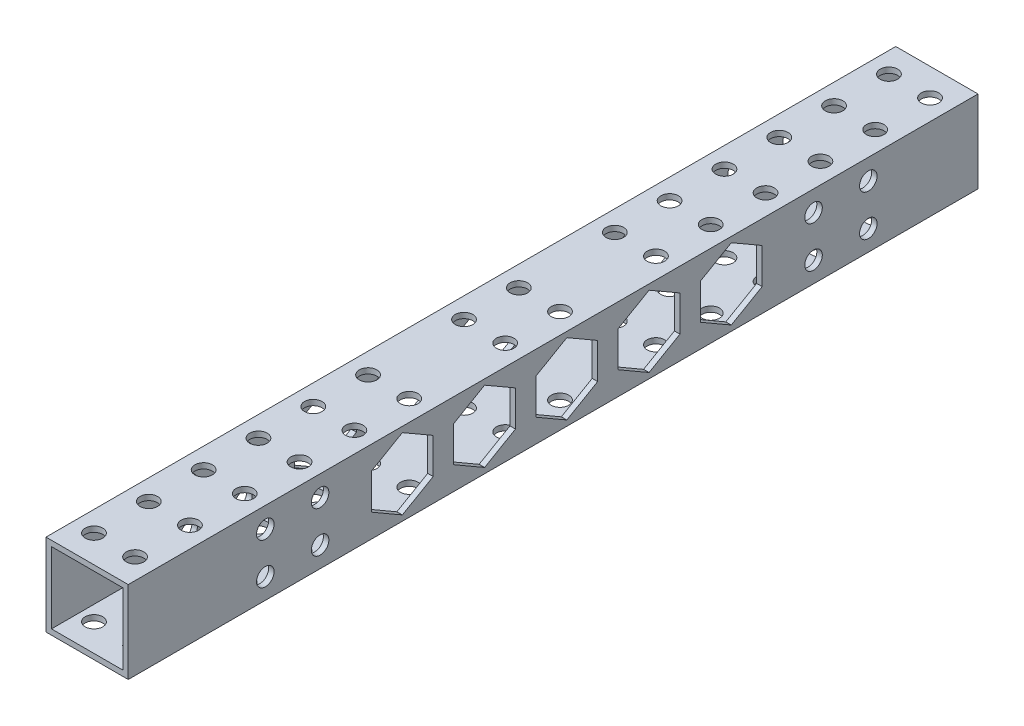
SolidWorks part; units mm, degrees
ref_plane "前视基准面" through (0, 0, 0) normal (0, 0, 1) x (1, 0, 0)
ref_plane "上视基准面" through (0, 0, 0) normal (0, 1, 0) x (1, 0, 0)
ref_plane "右视基准面" through (0, 0, 0) normal (1, 0, 0) x (0, 0, -1)
other "Configuration Table"
sketch "草图1" plane through (0, 0, 0) normal (0, 0, 1) x (1, 0, 0)
  line L1 (0, 0) -> (15, 0)
  line L2 (0, 0) -> (0, -15)
  line L3 (0, -15) -> (15, -15)
  line L4 (15, 0) -> (15, -15)
  dimension "D1" = 15
  dimension "D2" = 15
extrude "拉伸-薄壁1" add sketch "草图1" along normal blind 155 thin
sketch "草图2" plane through (15, 0, 0) normal (1, 0, 0) x (0, 0, -1)
  line L0 (-77.5, 0) -> (-77.5, -15) construction
  line L1 (-155, 0) -> (0, 0) construction
  line L2 (-155, -15) -> (0, -15) construction
  line L3 (-125, 0) -> (-125, -15) construction
  line L4 (-155, -15) -> (-155, 0) construction
  line L5 (-155, -7.5) -> (-125, -7.5) construction
  line L6 (-25, 0) -> (-25, -15) construction
  line L7 (0, -7.5) -> (-25, -7.5) construction
  line L8 (0, -15) -> (0, 0) construction
  line L9 (-105, -7.5) -> (-125, -7.5) construction
  line L10 (-105, -1) -> (-110.6292, -4.25)
  line L11 (-110.6292, -4.25) -> (-110.6292, -10.75)
  line L12 (-110.6292, -10.75) -> (-105, -14)
  line L13 (-105, -14) -> (-99.3708, -10.75)
  line L14 (-99.3708, -10.75) -> (-99.3708, -4.25)
  line L15 (-99.3708, -4.25) -> (-105, -1)
  line L16 (-84.3708, -10.75) -> (-84.3708, -4.25)
  line L17 (-84.3708, -4.25) -> (-90, -1)
  line L18 (-90, -1) -> (-95.6292, -4.25)
  line L19 (-95.6292, -4.25) -> (-95.6292, -10.75)
  line L20 (-95.6292, -10.75) -> (-90, -14)
  line L21 (-90, -14) -> (-84.3708, -10.75)
  line L22 (-69.3708, -10.75) -> (-69.3708, -4.25)
  line L23 (-69.3708, -4.25) -> (-75, -1)
  line L24 (-75, -1) -> (-80.6292, -4.25)
  line L25 (-80.6292, -4.25) -> (-80.6292, -10.75)
  line L26 (-80.6292, -10.75) -> (-75, -14)
  line L27 (-75, -14) -> (-69.3708, -10.75)
  line L28 (-54.3708, -10.75) -> (-54.3708, -4.25)
  line L29 (-54.3708, -4.25) -> (-60, -1)
  line L30 (-60, -1) -> (-65.6292, -4.25)
  line L31 (-65.6292, -4.25) -> (-65.6292, -10.75)
  line L32 (-65.6292, -10.75) -> (-60, -14)
  line L33 (-60, -14) -> (-54.3708, -10.75)
  line L34 (-39.3708, -10.75) -> (-39.3708, -4.25)
  line L35 (-39.3708, -4.25) -> (-45, -1)
  line L36 (-45, -1) -> (-50.6292, -4.25)
  line L37 (-50.6292, -4.25) -> (-50.6292, -10.75)
  line L38 (-50.6292, -10.75) -> (-45, -14)
  line L39 (-45, -14) -> (-39.3708, -10.75)
  circle A0 centre (-130, -3.75) radius 1.6
  circle A1 centre (-130, -11.25) radius 1.6
  circle A2 centre (-120, -11.25) radius 1.6
  circle A3 centre (-120, -3.75) radius 1.6
  circle A8 centre (-20, -3.75) radius 1.6
  circle A9 centre (-20, -11.25) radius 1.6
  circle A10 centre (-30, -11.25) radius 1.6
  circle A11 centre (-30, -3.75) radius 1.6
  circle A12 centre (-105, -7.5) radius 5.6292 construction
  dimension "D2" = 3.2
  dimension "D6" = 3.2
  dimension "D1" = 30
  dimension "D3" = 5
  dimension "D4" = 3.75
  dimension "D5" = 25
  dimension "D7" = 3.75
  dimension "D8" = 5
  dimension "D9" = 6.5
  dimension "D10" = 20
  dimension "D12" = 15
  dimension "D11" = 5
extrude "切除-拉伸1" cut sketch "草图2" against normal through all
sketch "草图3" plane through (0, 0, 0) normal (0, 1, 0) x (1, 0, 0)
  line L0 (7.5, 0) -> (7.5, -155) construction
  line L1 (15, 0) -> (0, 0) construction
  line L2 (15, -155) -> (0, -155) construction
  line L3 (15, -77.5) -> (0, -77.5) construction
  line L4 (15, -155) -> (15, 0) construction
  line L5 (0, -155) -> (0, 0) construction
  line L6 (0, -10) -> (15, -10) construction
  line L7 (0, -145) -> (15, -145) construction
  circle A0 centre (3.75, -5) radius 1.6
  circle A1 centre (11.25, -5) radius 1.6
  circle A2 centre (11.25, -15) radius 1.6
  circle A3 centre (3.75, -15) radius 1.6
  circle A8 centre (3.75, -25) radius 1.6
  circle A9 centre (11.25, -25) radius 1.6
  circle A10 centre (11.25, -35) radius 1.6
  circle A11 centre (3.75, -35) radius 1.6
  circle A12 centre (3.75, -45) radius 1.6
  circle A13 centre (11.25, -45) radius 1.6
  circle A14 centre (11.25, -55) radius 1.6
  circle A15 centre (3.75, -55) radius 1.6
  circle A16 centre (3.75, -72.5) radius 1.6
  circle A17 centre (11.25, -72.5) radius 1.6
  circle A18 centre (11.25, -82.5) radius 1.6
  circle A19 centre (3.75, -82.5) radius 1.6
  circle A20 centre (3.75, -100) radius 1.6
  circle A21 centre (11.25, -100) radius 1.6
  circle A22 centre (11.25, -110) radius 1.6
  circle A23 centre (3.75, -110) radius 1.6
  circle A24 centre (3.75, -120) radius 1.6
  circle A25 centre (11.25, -120) radius 1.6
  circle A26 centre (11.25, -130) radius 1.6
  circle A27 centre (3.75, -130) radius 1.6
  circle A28 centre (3.75, -140) radius 1.6
  circle A29 centre (11.25, -140) radius 1.6
  circle A30 centre (11.25, -150) radius 1.6
  circle A31 centre (3.75, -150) radius 1.6
  dimension "D1" = 3.2
  dimension "D7" = 3.2
  dimension "D2" = 3.75
  dimension "D3" = 10
  dimension "D4" = 5
  dimension "D6" = 10
  dimension "D8" = 5
  dimension "D9" = 3.75
  dimension "D5" = 3
extrude "切除-拉伸2" cut sketch "草图3" against normal through all
